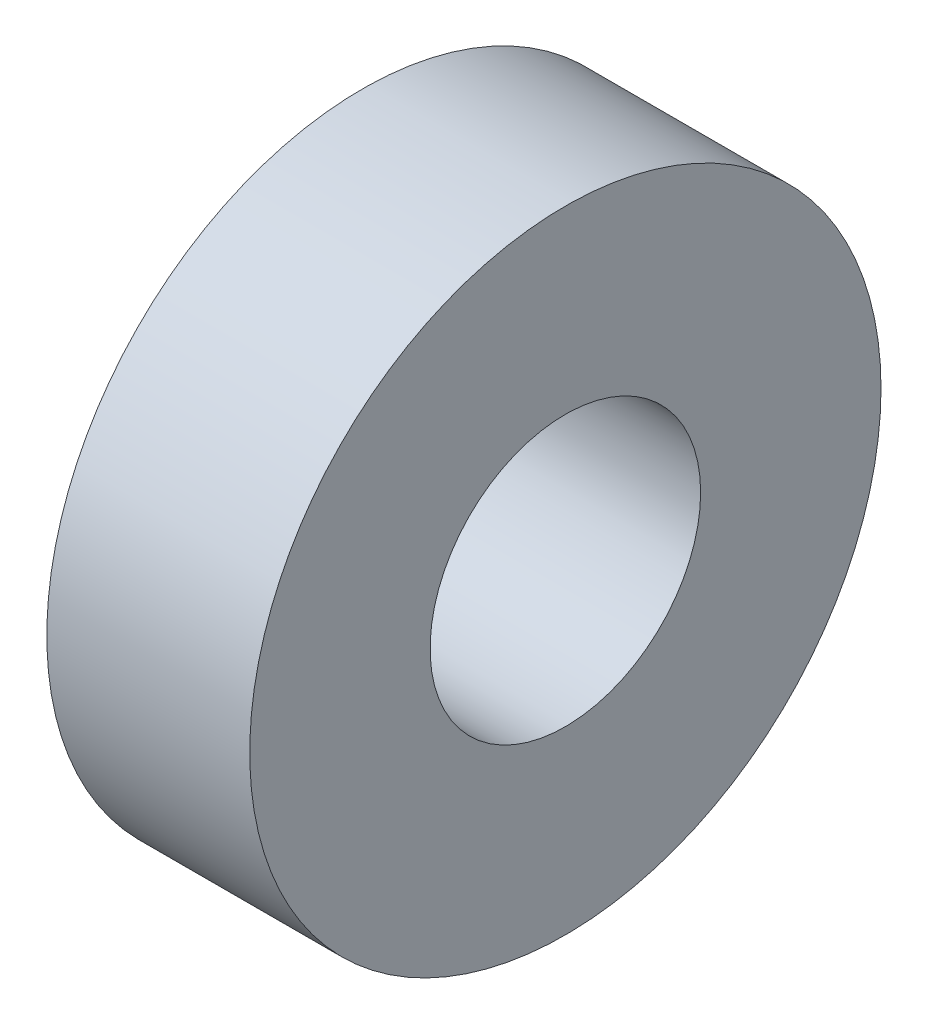
SolidWorks part; units mm, degrees
ref_plane "Front Plane" through (0, 0, 0) normal (0, 0, 1) x (1, 0, 0)
ref_plane "Top Plane" through (0, 0, 0) normal (0, 1, 0) x (1, 0, 0)
ref_plane "Right Plane" through (0, 0, 0) normal (1, 0, 0) x (0, 0, -1)
sketch "Sketch1" plane through (0, 0, 0) normal (1, 0, 0) x (0, 0, -1)
  circle A0 centre (0, 0) radius 38.1
  circle A1 centre (0, 0) radius 88.9
  dimension "D1" = 76.2
  dimension "D2" = 177.8
extrude "Boss-Extrude1" add sketch "Sketch1" along normal mid plane 57.15
